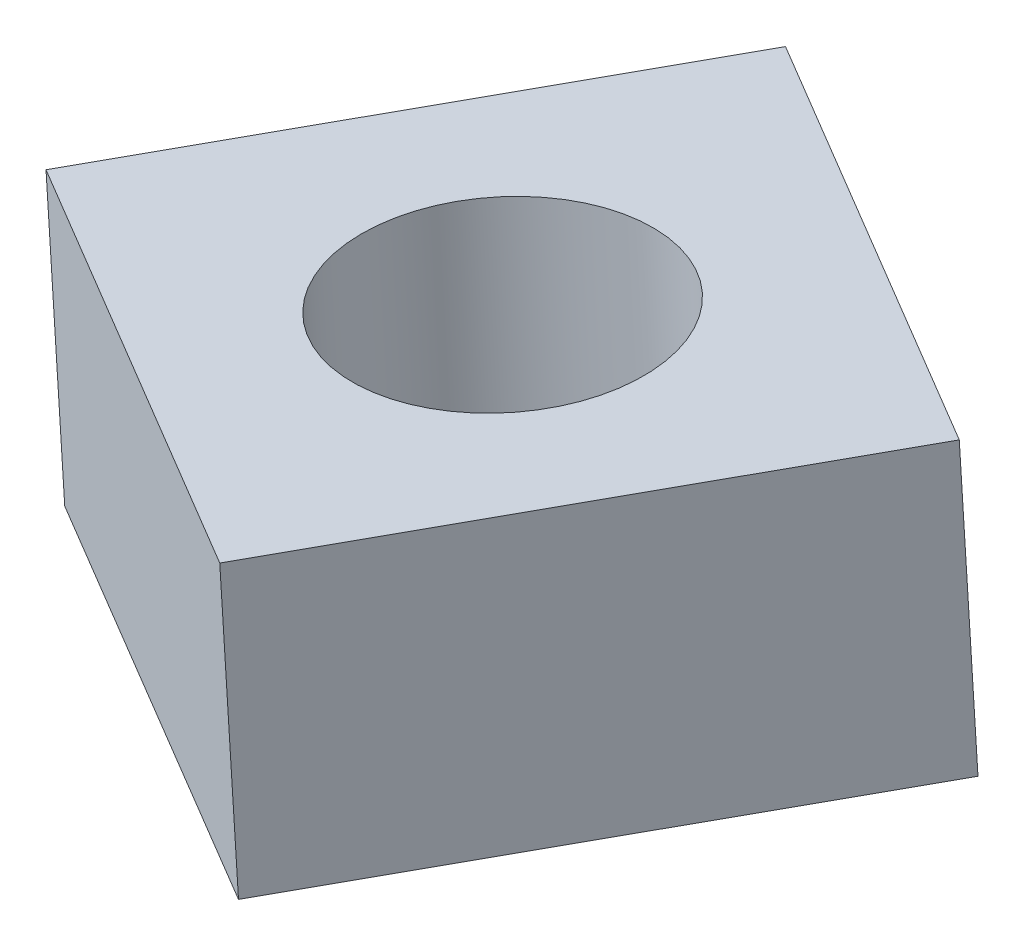
SolidWorks part; units mm, degrees
ref_plane "Plan1" through (0, 0, 0) normal (0, 0, 1) x (1, 0, 0)
ref_plane "Plan2" through (0, 0, 0) normal (0, 1, 0) x (1, 0, 0)
ref_plane "Plan3" through (0, 0, 0) normal (1, 0, 0) x (0, 0, -1)
ref_plane "Plan4" through (-26.8383, 415.17, 0.7013) normal (0.0645, -0.9979, -0.0017) x (0.9979, 0.0645, 0)
sketch "Esquisse1" plane through (-26.8383, 415.17, 0.7013) normal (0.0645, -0.9979, -0.0017) x (0.9979, 0.0645, 0)
  line L0 (1614.0497, 1079.5649) -> (1619.0446, 1071.4839)
  line L1 (1619.0446, 1071.4839) -> (1627.1255, 1076.4788)
  line L2 (1627.1255, 1076.4788) -> (1622.1306, 1084.5597)
  line L3 (1622.1306, 1084.5597) -> (1614.0497, 1079.5649)
  circle A0 centre (1620.5876, 1078.0218) radius 2.5
  dimension "D1" = 5
  dimension "D2" = 9.5
  dimension "D3" = 9.5
  dimension "D4" = 4.75
  dimension "D5" = 4.75
extrude "Base-Extrusion" add sketch "Esquisse1" against normal blind 5
cosmetic thread "Représentation de filetage1"
